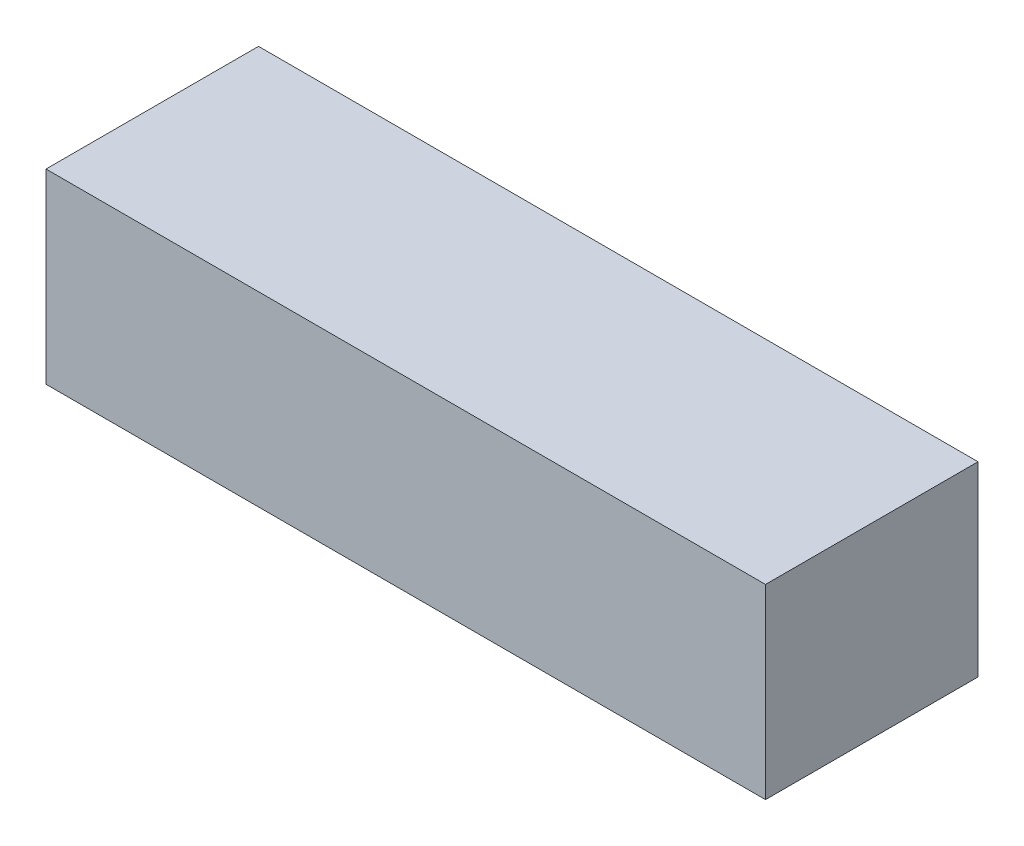
SolidWorks part; units mm, degrees
ref_plane "Front Plane" through (0, 0, 0) normal (0, 0, 1) x (1, 0, 0)
ref_plane "Top Plane" through (0, 0, 0) normal (0, 1, 0) x (1, 0, 0)
ref_plane "Right Plane" through (0, 0, 0) normal (1, 0, 0) x (0, 0, -1)
sketch "Sketch1" plane through (0, 0, 0) normal (1, 0, 0) x (0, 0, -1)
  line L0 (-7.239, 6.35) -> (7.239, 6.35)
  line L1 (7.239, 6.35) -> (7.239, -6.35)
  line L2 (7.239, -6.35) -> (-7.239, -6.35)
  line L3 (-7.239, -6.35) -> (-7.239, 6.35)
  dimension "D1" = 7.239
  dimension "D2" = 14.478
  dimension "D3" = 6.35
  dimension "D4" = 12.7
extrude "Boss-Extrude1" add sketch "Sketch1" along normal blind 49.022
